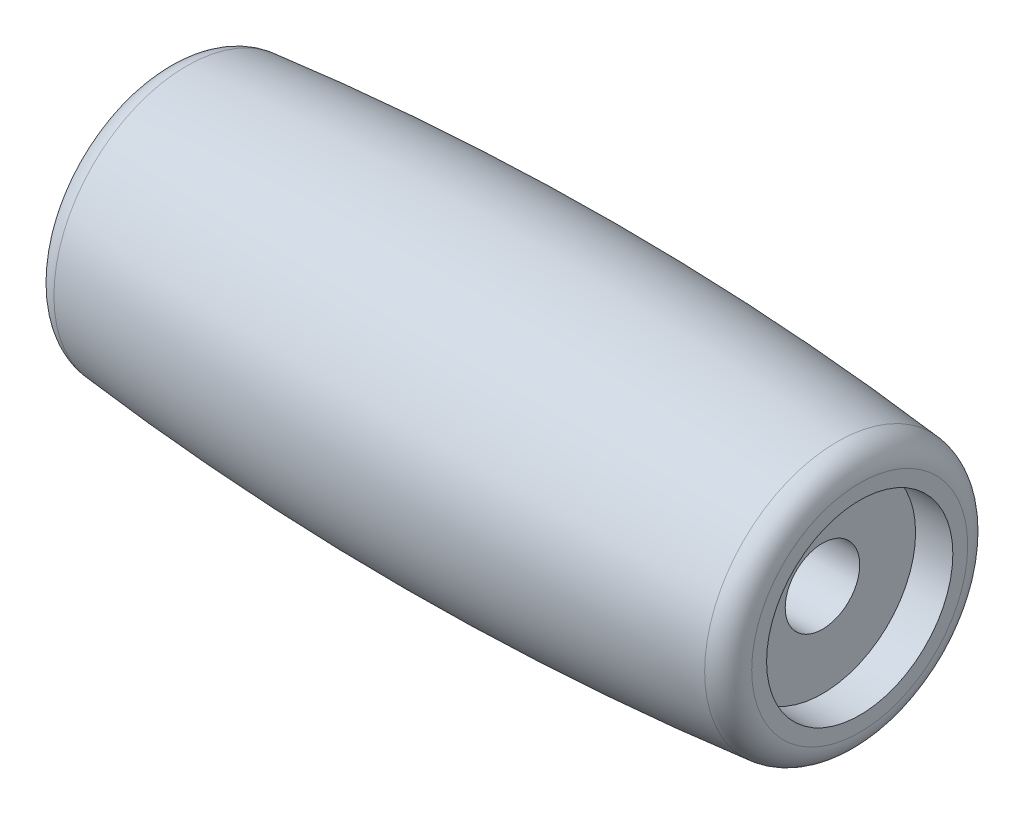
SolidWorks part; units mm, degrees
ref_plane "Front Plane" through (0, 0, 0) normal (0, 0, 1) x (1, 0, 0)
ref_plane "Top Plane" through (0, 0, 0) normal (0, 1, 0) x (1, 0, 0)
ref_plane "Right Plane" through (0, 0, 0) normal (1, 0, 0) x (0, 0, -1)
sketch "Sketch1" plane through (0, 0, 0) normal (0, 0, 1) x (1, 0, 0)
  line L0 (0, 0) -> (8.8884, 0) construction
  line L1 (0, 0) -> (0, 6) construction
  line L2 (-1.7479, 1.5) -> (1.7479, 1.5)
  line L3 (1.7479, 1.5) -> (12.5, 1.5)
  line L4 (12.5, 1.5) -> (12.5, 3.75)
  line L5 (12.5, 3.75) -> (14, 3.75)
  line L6 (14, 3.75) -> (14, 4.3486)
  line L7 (-14, 3.75) -> (-14, 4.3486)
  line L8 (-12.5, 1.5) -> (-12.5, 3.75)
  line L9 (-12.5, 3.75) -> (-14, 3.75)
  line L10 (-1.7479, 1.5) -> (-12.5, 1.5)
  arc A0 (-13.1, 5.3436) -> (13.1, 5.3436) centre (0, -125.0417) cw
  arc A1 (14, 4.3486) -> (13.1, 5.3436) centre (13, 4.3486) ccw
  arc A2 (-14, 4.3486) -> (-13.1, 5.3436) centre (-13, 4.3486) cw
  point P15 (0, 1.5)
  point P16 (0, 0)
  point P19 (14, 5.25)
  point P22 (-14, 5.25)
  dimension "D7" = 1
  dimension "D1" = 1.5
  dimension "D2" = 3.75
  dimension "D3" = 1.5
  dimension "D4" = 1.5
  dimension "D5" = 14
  dimension "D6" = 6
revolve "Revolve1" add sketch "Sketch1" angle 360 about L0
